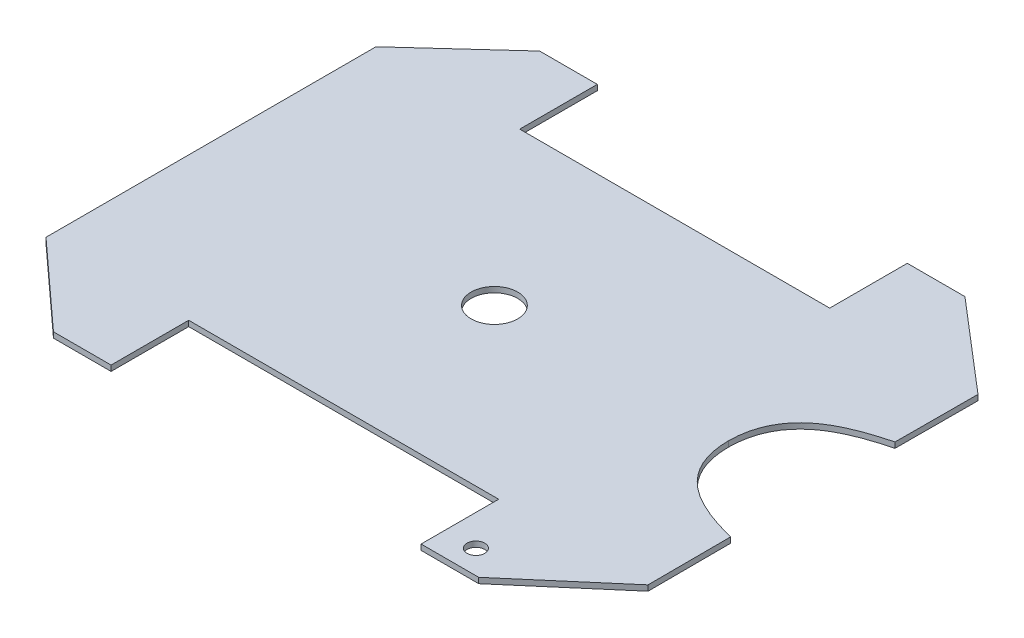
SolidWorks part; units mm, degrees
ref_plane "Спереди" through (0, 0, 0) normal (0, 0, 1) x (1, 0, 0)
ref_plane "Сверху" through (0, 0, 0) normal (0, 1, 0) x (1, 0, 0)
ref_plane "Справа" through (0, 0, 0) normal (1, 0, 0) x (0, 0, -1)
sketch "Эскиз1" plane through (0, 0, 0) normal (0, 1, 0) x (1, 0, 0)
  line L1 (-269.7922, 74.6607) -> (-269.7922, -223.012)
  line L2 (139.0683, -293.4928) -> (191.0683, -293.4928)
  line L3 (-140.5865, 145.1415) -> (-192.5865, 145.1415)
  line L4 (139.0683, -223.4928) -> (139.0683, -293.4928)
  line L5 (139.0683, 145.1415) -> (191.0683, 145.1415)
  line L6 (-140.5865, 75.1415) -> (-140.5865, 145.1415)
  line L7 (-0.7591, -12.2026) -> (-0.7591, 227.1905) construction
  line L8 (273.3416, 74.6607) -> (273.1017, 0.0307)
  line L9 (-140.5865, -223.4928) -> (139.0683, -223.4928)
  line L10 (139.0683, 75.1415) -> (139.0683, 145.1415)
  line L11 (-140.5865, 75.1415) -> (139.0683, 75.1415)
  line L12 (-140.5865, -223.4928) -> (-140.5865, -293.4928)
  line L13 (-140.5865, -293.4928) -> (-192.5865, -293.4928)
  line L14 (273.3416, -223.012) -> (273.1017, -148.382)
  line L17 (-326.8393, -74.1757) -> (107.7018, -74.1757) construction
  line L22 (-269.7922, 74.6607) -> (-192.5865, 145.1415)
  line L23 (-269.7922, -223.012) -> (-192.5865, -293.4928)
  line L24 (-263.7922, 74.6607) -> (-387.0064, 74.6607) construction
  line L25 (-269.7922, -223.012) -> (-392.2998, -223.012) construction
  line L26 (273.3416, -223.012) -> (191.0683, -293.4928)
  line L27 (273.3416, 74.6607) -> (191.0683, 145.1415)
  spline S0 degree 3 poles (273.1017, 0.0307) (239.4366, -8.8528) (197.437, -23.6267) (197.0474, -74.1757) knots 0 0 0 0 1 1 1 1
  spline S1 degree 3 poles (241.3333, -15.1188) (241.3449, -11.9635) (241.3327, -4.2402) (241.3148, -3.4392) knots 0 0 0 0 1 1 1 1 weights 1 0.504087 0.504087 1 construction
  spline S2 degree 3 poles (273.1017, -148.382) (239.4366, -139.4985) (197.437, -124.7247) (197.0474, -74.1757) knots 0 0 0 0 1 1 1 1
extrude "Вытянуть1" add sketch "Эскиз1" along normal blind 5
sketch "Эскиз2" plane through (0, 5, 0) normal (0, 1, 0) x (-1, 0, 0)
  circle A0 centre (14.23, 74.0267) radius 21
extrude "Вырез-Вытянуть1" cut sketch "Эскиз2" against normal through all
sketch "Sketch1" plane through (0, 5, 0) normal (0, 1, 0) x (1, 0, 0)
  circle A0 centre (167.053, -272.0659) radius 8
extrude "Cut-Extrude1" cut sketch "Sketch1" against normal through all
